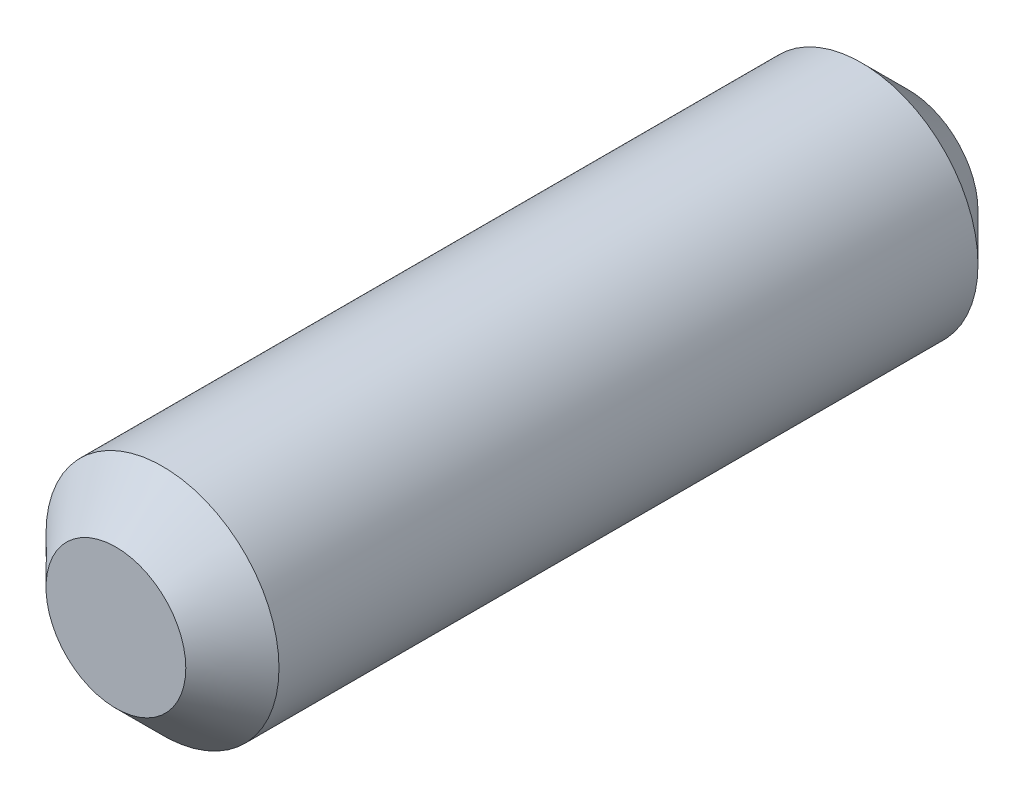
SolidWorks part; units mm, degrees
material "Plain Carbon Steel"
ref_plane "Front Plane" through (0, 0, 0) normal (0, 0, 1) x (1, 0, 0)
ref_plane "Top Plane" through (0, 0, 0) normal (0, 1, 0) x (1, 0, 0)
ref_plane "Right Plane" through (0, 0, 0) normal (1, 0, 0) x (0, 0, -1)
sketch "Sketch1" plane through (0, 0, 0) normal (0, 0, 1) x (1, 0, 0)
  circle A0 centre (0, 0) radius 2.5
  dimension "D1" = 5
extrude "Boss-Extrude1" add sketch "Sketch1" along normal mid plane 17
chamfer "Chamfer1" distance 1 angle 45 2 edges at (2.5, 0, -8.5) (2.5, 0, 8.5)
